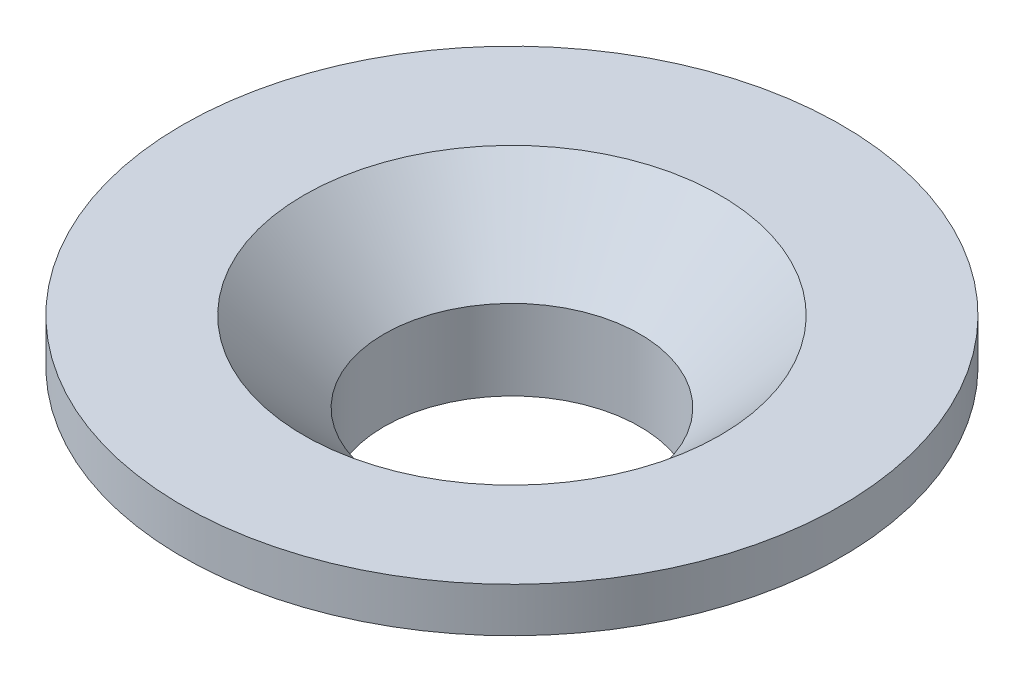
SolidWorks part; units mm, degrees
ref_plane "Płaszczyzna przednia" through (0, 0, 0) normal (0, 0, 1) x (1, 0, 0)
ref_plane "Płaszczyzna górna" through (0, 0, 0) normal (0, 1, 0) x (1, 0, 0)
ref_plane "Płaszczyzna prawa" through (0, 0, 0) normal (1, 0, 0) x (0, 0, -1)
sketch "Sketch1" plane through (0, 0, 0) normal (0, 0, 1) x (1, 0, 0)
  line L1 (0, 5) -> (6.82, 5)
  line L2 (6.82, 5) -> (6.82, 2.5)
  line L5 (-11.68, 6.1336) -> (-11.68, -4.0668)
  line L10 (0, 5) -> (-4.5, 0.5)
  line L11 (-2.5, 0) -> (-2.5, -4)
  line L12 (-4.5, 0.5) -> (-4.5, -4)
  line L13 (-4.5, -4) -> (-2.5, -4)
  line L14 (0, 2.5) -> (6.82, 2.5)
  circle A2 centre (0, 0) radius 2.5
  dimension "D8" = 4
  dimension "D6" = 4.5
  dimension "D2" = 5
  dimension "D3" = 18.5
  dimension "D4" = 2.5
  dimension "D7" = 135
  dimension "D11" = 2
  dimension "7.18" = 7.18
revolve "Revolve1" add sketch "Sketch1" angle 360 about L5
